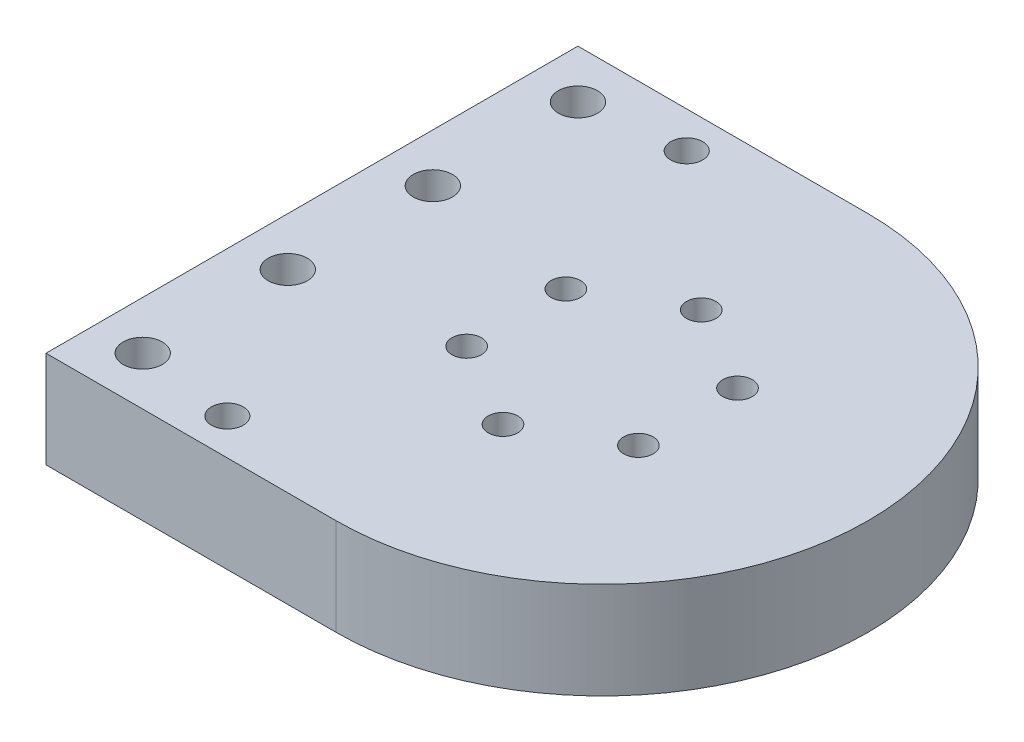
SolidWorks part; units mm, degrees
ref_plane "前视基准面" through (0, 0, 0) normal (0, 0, 1) x (1, 0, 0)
ref_plane "上视基准面" through (0, 0, 0) normal (0, 1, 0) x (1, 0, 0)
ref_plane "右视基准面" through (0, 0, 0) normal (1, 0, 0) x (0, 0, -1)
sketch "草图1" plane through (0, 0, 0) normal (0, 1, 0) x (1, 0, 0)
  line L6 (0, 27.5) -> (-20, 27.5)
  line L7 (-20, 27.5) -> (-20, -27.5)
  line L8 (-20, -27.5) -> (0, -27.5)
  line L9 (0, 0) -> (-20, 0) construction
  line L10 (-15, 23.75) -> (-15, -23.75) construction
  line L11 (-20, 27.5) -> (-30, 27.5)
  line L12 (-20, 27.5) -> (-20, -27.5)
  line L13 (-20, -27.5) -> (-30, -27.5)
  line L14 (-30, 27.5) -> (-30, -27.5)
  line L15 (-25, 27.5) -> (-25, 22.5) construction
  line L16 (-25, 22.5) -> (-25, 7.5) construction
  line L17 (-25, 7.5) -> (-25, -7.5) construction
  line L18 (-25, -7.5) -> (-25, -22.5) construction
  line L19 (-25, -22.5) -> (-25, -27.5) construction
  circle A1 centre (0, 0) radius 10.25 construction
  circle A2 centre (0, 10.25) radius 1.525
  circle A3 centre (8.8768, 5.125) radius 1.525
  circle A4 centre (8.8768, -5.125) radius 1.525
  circle A5 centre (0, -10.25) radius 1.525
  circle A6 centre (-15, 23.75) radius 1.65
  circle A7 centre (-15, -23.75) radius 1.65
  arc A8 (0, 27.5) -> (0, -27.5) centre (0, 0) cw
  circle A9 centre (-8.8768, -5.125) radius 1.525
  circle A10 centre (-8.8768, 5.125) radius 1.525
  circle A11 centre (-25, 22.5) radius 2.025
  circle A12 centre (-25, 7.5) radius 2.025
  circle A13 centre (-25, -7.5) radius 2.025
  circle A14 centre (-25, -22.5) radius 2.025
  point P14 (-15, 0)
  point P23 (0, 0)
  dimension "D1" = 55
  dimension "D4" = 20.5
  dimension "D5" = 3.05
  dimension "D7" = 3.3
  dimension "D11" = 4.05
  dimension "D2" = 20
  dimension "D3" = 10
  dimension "D8" = 47.5
  dimension "D9" = 5
  dimension "D10" = 5
  dimension "D6" = 6
extrude "凸台-拉伸1" add sketch "草图1" along normal blind 10
